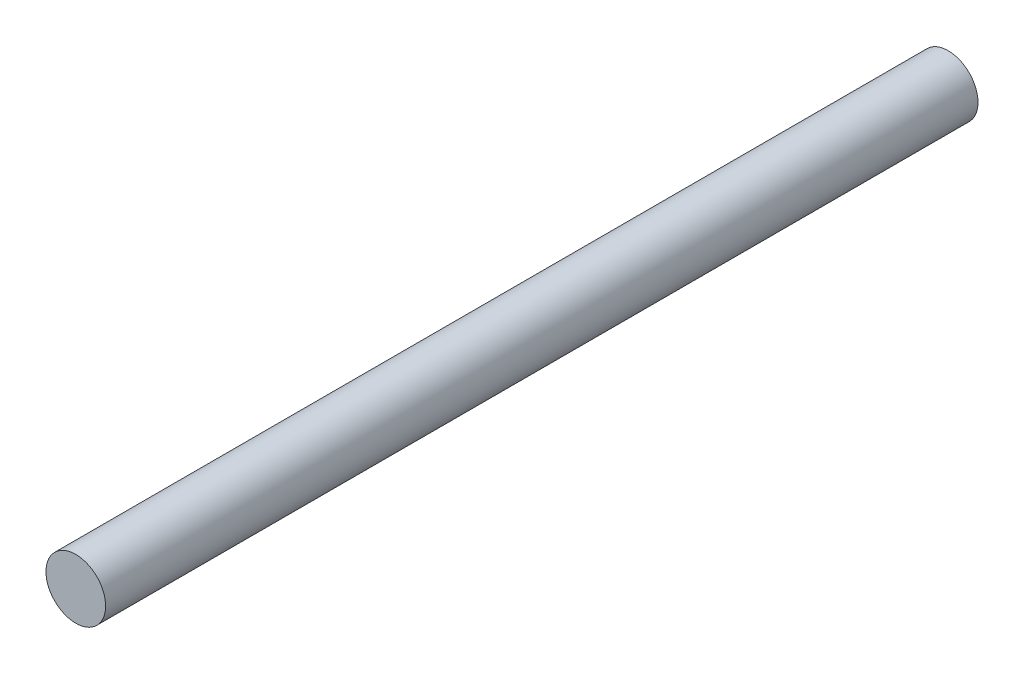
SolidWorks part; units mm, degrees
material "AISI 1020"
ref_plane "Alzado" through (0, 0, 0) normal (0, 0, 1) x (1, 0, 0)
ref_plane "Planta" through (0, 0, 0) normal (0, 1, 0) x (1, 0, 0)
ref_plane "Vista lateral" through (0, 0, 0) normal (1, 0, 0) x (0, 0, -1)
sketch "Croquis1" plane through (0, 0, 0) normal (0, 0, 1) x (1, 0, 0)
  circle A0 centre (0, 0) radius 4
  dimension "D1" = 8
extrude "Saliente-Extruir1" add sketch "Croquis1" along normal blind 117
